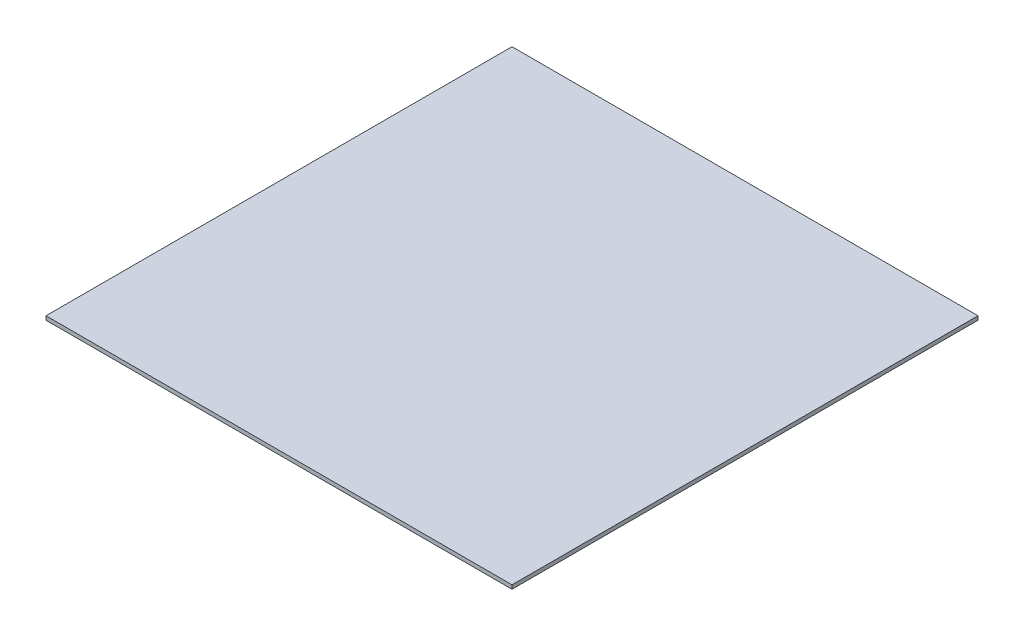
SolidWorks part; units mm, degrees
ref_plane "Front Plane" through (0, 0, 0) normal (0, 0, 1) x (1, 0, 0)
ref_plane "Top Plane" through (0, 0, 0) normal (0, 1, 0) x (1, 0, 0)
ref_plane "Right Plane" through (0, 0, 0) normal (1, 0, 0) x (0, 0, -1)
sketch "Sketch1" plane through (0, 0, 0) normal (0, 1, 0) x (1, 0, 0)
  line L1 (-76.2, -76.2) -> (76.2, -76.2)
  line L2 (-76.2, -76.2) -> (-76.2, 76.2)
  line L3 (-76.2, 76.2) -> (76.2, 76.2)
  line L4 (76.2, -76.2) -> (76.2, 76.2)
  line L5 (-76.2, -76.2) -> (76.2, 76.2) construction
  line L6 (-76.2, 76.2) -> (76.2, -76.2) construction
  point P0 (0, 0)
  dimension "D1" = 152.4
  dimension "D2" = 152.4
  dimension "D3" = 76.2
extrude "Boss-Extrude1" add sketch "Sketch1" along normal blind 1.27
